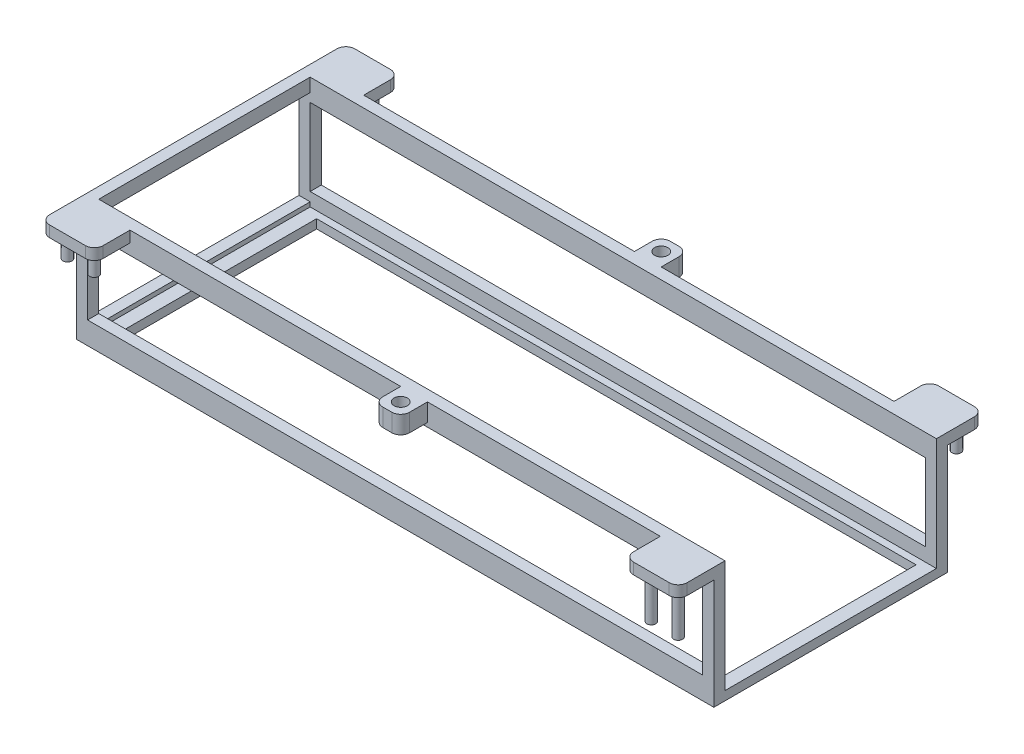
SolidWorks part; units mm, degrees
ref_plane "Front Plane" through (0, 0, 0) normal (0, 0, 1) x (1, 0, 0)
ref_plane "Top Plane" through (0, 0, 0) normal (0, 1, 0) x (1, 0, 0)
ref_plane "Right Plane" through (0, 0, 0) normal (1, 0, 0) x (0, 0, -1)
sketch "Sketch1" plane through (0, 0, 0) normal (0, 1, 0) x (1, 0, 0)
  line L1 (-72.7, -26.2) -> (72.7, -26.2)
  line L2 (-72.7, -26.2) -> (-72.7, 26.2)
  line L3 (-72.7, 26.2) -> (72.7, 26.2)
  line L4 (72.7, -26.2) -> (72.7, 26.2)
  line L5 (-72.7, -26.2) -> (72.7, 26.2) construction
  line L6 (-72.7, 26.2) -> (72.7, -26.2) construction
  point P0 (0, 0)
  dimension "D1" = 145.4
  dimension "D2" = 52.4
extrude "Boss-Extrude1" add sketch "Sketch1" along normal blind 27.2
sketch "Sketch2" plane through (0, 27.2, 0) normal (0, 1, 0) x (1, 0, 0)
  line L1 (-70.2, -23.7) -> (70.2, -23.7)
  line L2 (-70.2, -23.7) -> (-70.2, 23.7)
  line L3 (-70.2, 23.7) -> (70.2, 23.7)
  line L4 (70.2, -23.7) -> (70.2, 23.7)
  line L5 (-70.2, -23.7) -> (70.2, 23.7) construction
  line L6 (-70.2, 23.7) -> (70.2, -23.7) construction
  point P0 (0, 0)
  dimension "D1" = 140.4
  dimension "D2" = 47.4
extrude "Cut-Extrude1" cut sketch "Sketch2" against normal blind 25.2
sketch "Sketch3" plane through (70.2, 0, 0) normal (-1, 0, 0) x (0, 0, 1)
  line L0 (23.7, 2) -> (23.7, 27.2) construction
  line L1 (-22.7, 27.2) -> (23.7, 27.2)
  line L2 (-22.7, 27.2) -> (-22.7, 2)
  line L3 (-22.7, 2) -> (23.7, 2)
  line L4 (23.7, 27.2) -> (23.7, 2)
  line L5 (-22.7, 27.2) -> (23.7, 2) construction
  line L6 (-22.7, 2) -> (23.7, 27.2) construction
  line L7 (23.7, 2) -> (-23.7, 2) construction
  point P0 (0.5, 14.6)
extrude "Cut-Extrude2" cut sketch "Sketch3" against normal blind 25.2
sketch "Sketch4" plane through (0, 27.2, 0) normal (0, 1, 0) x (1, 0, 0)
  line L0 (-72.7, -26.2) -> (72.7, -26.2) construction
  line L1 (0, -26.2) -> (6, -26.2)
  line L2 (0, -26.2) -> (0, -32.2)
  line L3 (0, -32.2) -> (6, -32.2)
  line L4 (6, -26.2) -> (6, -32.2)
  line L5 (72.7, 26.2) -> (-72.7, 26.2) construction
  line L6 (0, 26.2) -> (6, 26.2)
  line L7 (0, 26.2) -> (0, 32.2)
  line L8 (0, 32.2) -> (6, 32.2)
  line L9 (6, 26.2) -> (6, 32.2)
  dimension "D1" = 6
  dimension "D2" = 6
  dimension "D3" = 6
  dimension "D4" = 6
extrude "Boss-Extrude2" add sketch "Sketch4" against normal blind 4
fillet "Fillet1" radius 2 2 edges at (6, 25.2, -32.2) (0, 25.2, -32.2)
fillet "Fillet2" radius 2 2 edges at (0, 25.2, 32.2) (6, 25.2, 32.2)
sketch "Sketch7" plane through (0, 23.2, 0) normal (0, -1, 0) x (-1, 0, 0)
  line L0 (0, 26.2) -> (-6, 26.2) construction
  line L1 (72.7, -26.2) -> (-72.7, -26.2) construction
  circle A0 centre (-3, -29.2) radius 1.5
  circle A1 centre (-3, 29.2) radius 1.5
  dimension "D1" = 3
  dimension "D2" = 3
  dimension "D3" = 3
  dimension "D4" = 3
extrude "Cut-Extrude4" cut sketch "Sketch7" against normal blind 4
sketch "Sketch8" plane through (0, 27.2, 0) normal (0, 1, 0) x (1, 0, 0)
  line L0 (72.7, 26.2) -> (6, 26.2) construction
  line L1 (72.7, -26.2) -> (70.2, -26.2)
  line L2 (72.7, -26.2) -> (72.7, 26.2)
  line L3 (72.7, 26.2) -> (70.2, 26.2)
  line L4 (70.2, -26.2) -> (70.2, 26.2)
  dimension "D1" = 2.5
extrude "Cut-Extrude5" cut sketch "Sketch8" against normal blind 43
sketch "Sketch9" plane through (-72.7, 0, 0) normal (-1, 0, 0) x (0, 0, 1)
  line L0 (26.2, 27.2) -> (26.2, 0) construction
  line L1 (-23.7, 3) -> (23.7, 3)
  line L2 (-23.7, 3) -> (-23.7, 24.2)
  line L3 (-23.7, 24.2) -> (23.7, 24.2)
  line L4 (23.7, 3) -> (23.7, 24.2)
  line L5 (-23.7, 3) -> (23.7, 24.2) construction
  line L6 (-23.7, 24.2) -> (23.7, 3) construction
  line L7 (-26.2, 27.2) -> (-26.2, 0) construction
  line L8 (-26.2, 27.2) -> (26.2, 27.2) construction
  line L9 (-26.2, 0) -> (26.2, 0) construction
  point P0 (0, 13.6)
  dimension "D1" = 2.5
  dimension "D2" = 2.5
  dimension "D3" = 3
  dimension "D4" = 3
extrude "Cut-Extrude6" cut sketch "Sketch9" against normal blind 43
sketch "Sketch11" plane through (0, 0, -26.2) normal (0, 0, -1) x (-1, 0, 0)
  line L0 (-70.2, 0) -> (72.7, 0) construction
  line L1 (-67.7, 22.2881) -> (70.2, 22.2881)
  line L2 (-67.7, 22.2881) -> (-67.7, 5)
  line L3 (-67.7, 5) -> (70.2, 5)
  line L4 (70.2, 22.2881) -> (70.2, 5)
  line L5 (-70.2, 0) -> (-70.2, 27.2) construction
  line L6 (72.7, 27.2) -> (72.7, 0) construction
  dimension "D1" = 5
  dimension "D2" = 2.5
  dimension "D3" = 2.5
extrude "Cut-Extrude7" cut sketch "Sketch11" against normal blind 59
sketch "Sketch12" plane through (0, 0, 0) normal (0, -1, 0) x (-1, 0, 0)
  line L0 (-70.2, -26.2) -> (-70.2, 26.2) construction
  line L1 (67.2, 22.1402) -> (-67.2, 22.1402)
  line L2 (67.2, 22.1402) -> (67.2, -22.1402)
  line L3 (67.2, -22.1402) -> (-67.2, -22.1402)
  line L4 (-67.2, 22.1402) -> (-67.2, -22.1402)
  line L5 (67.2, 22.1402) -> (-67.2, -22.1402) construction
  line L6 (67.2, -22.1402) -> (-67.2, 22.1402) construction
  point P0 (0, 0)
  dimension "D1" = 3
extrude "Cut-Extrude8" cut sketch "Sketch12" against normal blind 10
sketch "Sketch16" plane through (0, 0, -26.2) normal (0, 0, -1) x (-1, 0, 0)
  line L0 (-70.2, 0) -> (-70.2, 27.2) construction
  line L1 (-70.2, 24.7) -> (-58.2, 24.7)
  line L2 (-70.2, 24.7) -> (-70.2, 27.2)
  line L3 (-70.2, 27.2) -> (-58.2, 27.2)
  line L4 (-58.2, 24.7) -> (-58.2, 27.2)
  line L5 (-70.2, 27.2) -> (-6, 27.2) construction
  dimension "D1" = 12
  dimension "D2" = 2.5
extrude "Boss-Extrude4" add sketch "Sketch16" along normal blind 8
fillet "Fillet3" radius 2 2 edges at (70.2, 25.95, -34.2) (58.2, 25.95, -34.2)
sketch "Sketch17" plane through (0, 24.7, 0) normal (0, -1, 0) x (-1, 0, 0)
  line L0 (-58.2, 32.2) -> (-58.2, 26.2) construction
  line L1 (-70.2, 32.2) -> (-70.2, 26.2) construction
  line L2 (-70.2, 26.2) -> (72.7, 26.2) construction
  circle A0 centre (-67.2, 31.2) radius 1
  circle A1 centre (-61.2, 31.2) radius 1
  dimension "D1" = 2
  dimension "D2" = 2
  dimension "D3" = 6
  dimension "D4" = 3
  dimension "D5" = 3
  dimension "D6" = 5
extrude "Boss-Extrude5" add sketch "Sketch17" along normal blind 5
sketch "Sketch18" plane through (0, 0, 26.2) normal (0, 0, 1) x (1, 0, 0)
  line L1 (70.2, 27.2) -> (58.2, 27.2)
  line L2 (70.2, 27.2) -> (70.2, 24.7)
  line L3 (70.2, 24.7) -> (58.2, 24.7)
  line L4 (58.2, 27.2) -> (58.2, 24.7)
  dimension "D1" = 2.5
  dimension "D2" = 12
extrude "Boss-Extrude6" add sketch "Sketch18" along normal blind 8
fillet "Fillet4" radius 2 2 edges at (58.2, 25.95, 34.2) (70.2, 25.95, 34.2)
sketch "Sketch19" plane through (0, 24.7, 0) normal (0, -1, 0) x (-1, 0, 0)
  line L0 (-58.2, -32.2) -> (-58.2, -26.2) construction
  line L1 (-70.2, -32.2) -> (-70.2, -26.2) construction
  line L2 (-58.2, -26.2) -> (-70.2, -26.2) construction
  circle A0 centre (-67.2, -31.2) radius 1
  circle A1 centre (-61.2, -31.2) radius 1
  dimension "D1" = 2
  dimension "D2" = 2
  dimension "D3" = 6
  dimension "D4" = 3
  dimension "D5" = 3
  dimension "D6" = 5
extrude "Boss-Extrude7" add sketch "Sketch19" along normal blind 10
sketch "Sketch20" plane through (0, 0, 26.2) normal (0, 0, 1) x (1, 0, 0)
  line L1 (-72.7, 27.2) -> (-60.7, 27.2)
  line L2 (-72.7, 27.2) -> (-72.7, 24.7)
  line L3 (-72.7, 24.7) -> (-60.7, 24.7)
  line L4 (-60.7, 27.2) -> (-60.7, 24.7)
  dimension "D1" = 2.5
  dimension "D2" = 12
extrude "Boss-Extrude8" add sketch "Sketch20" along normal blind 8
fillet "Fillet5" radius 2 2 edges at (-60.7, 25.95, 34.2) (-72.7, 25.95, 34.2)
sketch "Sketch21" plane through (0, 24.7, 0) normal (0, -1, 0) x (-1, 0, 0)
  line L0 (72.7, -32.2) -> (72.7, -26.2) construction
  line L1 (60.7, -32.2) -> (60.7, -26.2) construction
  line L2 (72.7, -26.2) -> (60.7, -26.2) construction
  circle A0 centre (63.7, -31.2) radius 1
  circle A1 centre (69.7, -31.2) radius 1
  dimension "D1" = 2
  dimension "D2" = 2
  dimension "D3" = 6
  dimension "D4" = 3
  dimension "D5" = 3
  dimension "D6" = 5
extrude "Boss-Extrude9" add sketch "Sketch21" along normal blind 5
sketch "Sketch22" plane through (0, 0, -26.2) normal (0, 0, -1) x (-1, 0, 0)
  line L1 (72.7, 27.2) -> (60.7, 27.2)
  line L2 (72.7, 27.2) -> (72.7, 24.7)
  line L3 (72.7, 24.7) -> (60.7, 24.7)
  line L4 (60.7, 27.2) -> (60.7, 24.7)
  dimension "D1" = 2.5
  dimension "D2" = 12
extrude "Boss-Extrude10" add sketch "Sketch22" along normal blind 8
fillet "Fillet6" radius 2 2 edges at (-60.7, 25.95, -34.2) (-72.7, 25.95, -34.2)
sketch "Sketch23" plane through (0, 24.7, 0) normal (0, -1, 0) x (-1, 0, 0)
  line L0 (60.7, 32.2) -> (60.7, 26.2) construction
  line L2 (60.7, 26.2) -> (72.7, 26.2) construction
  circle A0 centre (63.7, 31.2) radius 1
  circle A1 centre (69.7, 31.2) radius 1
  dimension "D1" = 2
  dimension "D2" = 2
  dimension "D3" = 6
  dimension "D4" = 3
  dimension "D6" = 5
  dimension "D7" = 5
extrude "Boss-Extrude11" add sketch "Sketch23" along normal blind 5
